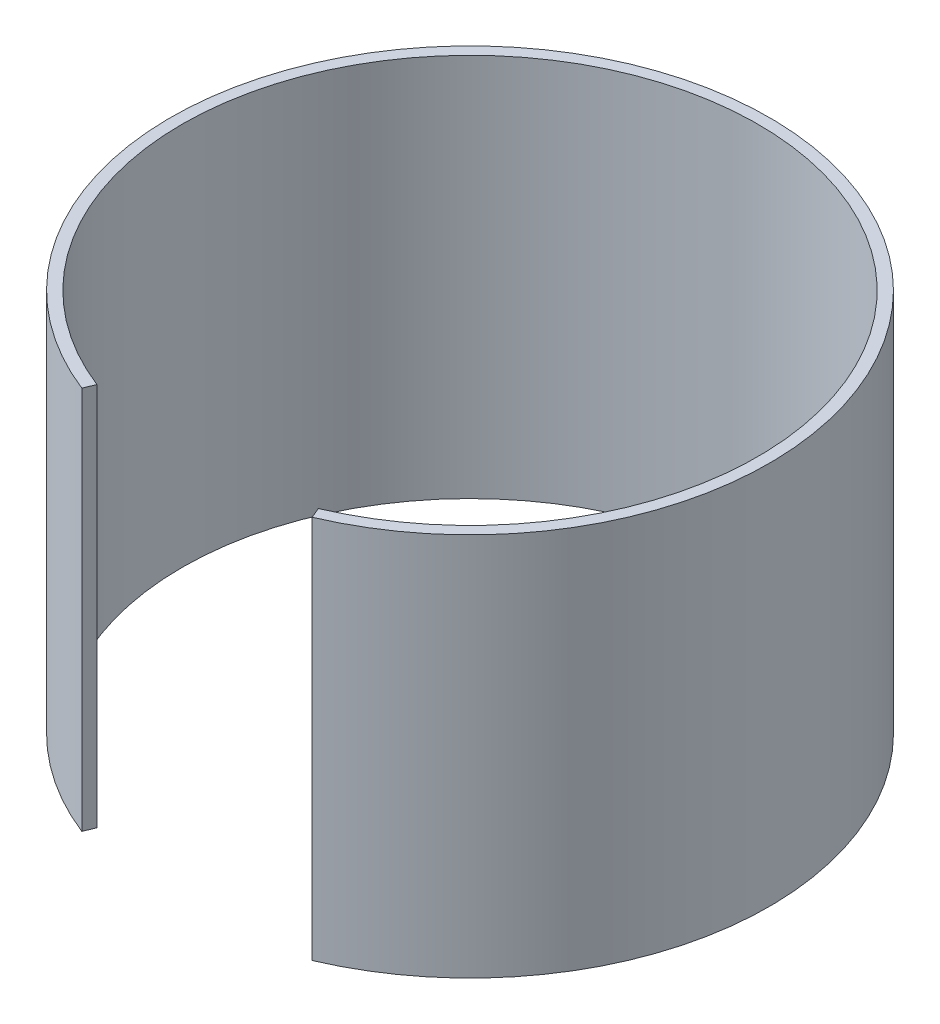
SolidWorks part; units mm, degrees
ref_plane "Front Plane" through (0, 0, 0) normal (0, 0, 1) x (1, 0, 0)
ref_plane "Top Plane" through (0, 0, 0) normal (0, 1, 0) x (1, 0, 0)
ref_plane "Right Plane" through (0, 0, 0) normal (1, 0, 0) x (0, 0, -1)
sketch "Sketch2" plane through (0, 0, 0) normal (0, 1, 0) x (1, 0, 0)
  line L0 (-14.2507, -36.3031) -> (-13.6766, -34.9171)
  line L1 (15.3094, -35.8695) -> (14.7353, -34.4836)
  line L2 (0, 0) -> (0, -95.446) construction
  arc A0 (14.7353, -34.4836) -> (-13.6766, -34.9171) centre (0, 0) ccw
  arc A1 (15.3094, -35.8695) -> (-14.2507, -36.3031) centre (0, 0) ccw
  dimension "D1" = 75
  dimension "D2" = 78
  dimension "D3" = 22.5
  dimension "D4" = 22.5
extrude "Boss-Extrude3" add sketch "Sketch2" along normal blind 50
